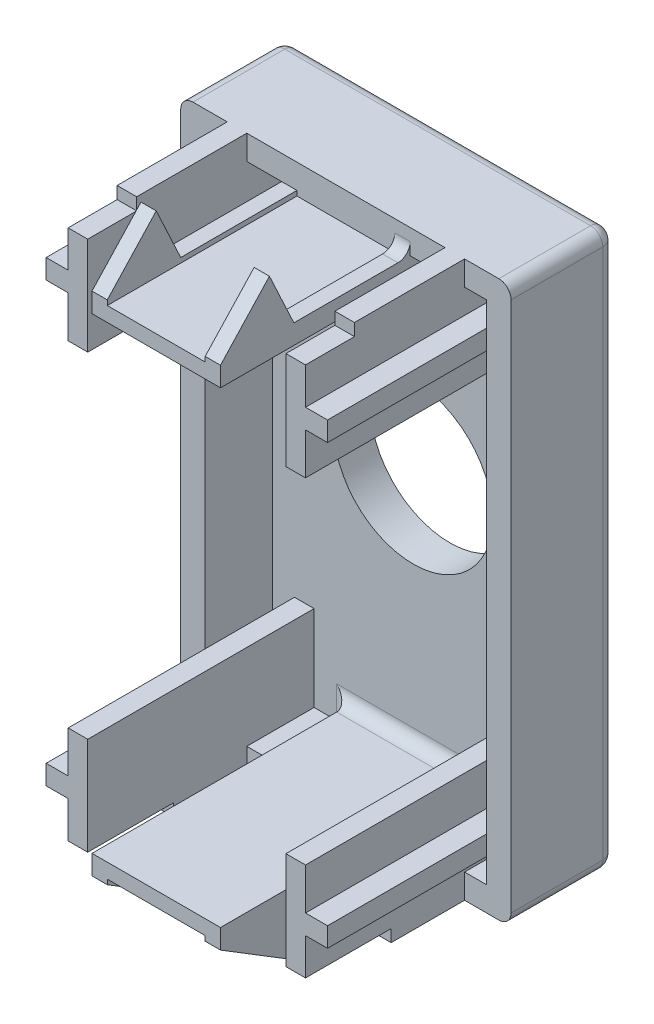
SolidWorks part; units mm, degrees
material "Сталь 3 ГОСТ 535-88"
ref_plane "Спереди" through (0, 0, 0) normal (0, 0, 1) x (1, 0, 0)
ref_plane "Сверху" through (0, 0, 0) normal (0, 1, 0) x (1, 0, 0)
ref_plane "Справа" through (0, 0, 0) normal (1, 0, 0) x (0, 0, -1)
sketch "Эскиз1" plane through (0, 0, 0) normal (0, 0, 1) x (1, 0, 0)
  line L0 (0, 22.7) -> (27, 22.7) construction
  line L1 (0, 0) -> (27, 0)
  line L2 (0, 0) -> (0, 45.4)
  line L3 (0, 45.4) -> (27, 45.4)
  line L4 (27, 0) -> (27, 45.4)
  circle A0 centre (13.5, 22.7) radius 6.5
  dimension "D3" = 13
  dimension "D1" = 27
  dimension "D2" = 45.4
extrude "Бобышка-Вытянуть1" add sketch "Эскиз1" along normal blind 8.5
ref_plane "Плоскость1" through (3, 0, 0) normal (1, 0, 0) x (0, 0, -1)
sketch "Эскиз2" plane through (3, 0, 0) normal (1, 0, 0) x (0, 0, -1)
  line L0 (0, 0) -> (0, 5) construction
  line L2 (0, 45.4) -> (0, 40.4) construction
  line L3 (0, 40.4) -> (0, 5)
  arc A0 (0, 5) -> (0, 40.4) centre (156.145, 22.7) cw
  point P3 (0, 0)
  point P9 (0, 0)
  point P10 (0, 0)
  point P11 (0, 0)
  dimension "D1" = 5
  dimension "D3" = 1
  dimension "D2" = 5
extrude "Вырез-Вытянуть1" cut sketch "Эскиз2" along normal offset from surface (21 mm away) 3 up to face at (27, 22.7, 4.25)
sketch "Эскиз3" plane through (0, 0, 8.5) normal (0, 0, 1) x (1, 0, 0)
  line L0 (25, 2) -> (25, 43.4)
  line L1 (27, 0) -> (0, 0) construction
  line L2 (27, 0) -> (27, 45.4) construction
  line L3 (27, 45.4) -> (0, 45.4) construction
  line L4 (0, 0) -> (0, 45.4) construction
  line L5 (25, 43.4) -> (2, 43.4)
  line L6 (2, 2) -> (2, 43.4)
  line L7 (25, 2) -> (2, 2)
  dimension "D1" = 2
extrude "Вырез-Вытянуть2" cut sketch "Эскиз3" against normal blind 5.5
sketch "Эскиз4" plane through (0, 0, 3) normal (0, 0, 1) x (1, 0, 0)
  line L0 (3.8, 45.4) -> (3.8, 41.4)
  line L1 (25, 43.4) -> (2, 43.4) construction
  line L2 (3.8, 41.4) -> (2, 41.4)
  line L3 (2, 43.4) -> (2, 2) construction
  line L4 (2, 41.4) -> (2, 39.8)
  line L5 (2, 39.8) -> (3.8, 39.8)
  line L6 (3.8, 39.8) -> (3.8, 36.4)
  line L7 (3.8, 36.4) -> (5.4, 36.4)
  line L8 (5.4, 36.4) -> (5.4, 45.4)
  line L10 (5.4, 45.4) -> (3.8, 45.4)
  line L11 (3.8, 39.8) -> (3.8, 41.4) construction
  line L12 (13.5, 43.4) -> (13.5, 2) construction
  line L13 (2, 2) -> (25, 2) construction
  line L14 (25, 22.7) -> (2, 22.7) construction
  line L15 (25, 2) -> (25, 43.4) construction
  line L16 (2, 43.4) -> (2, 2) construction
  line L17 (23.2, 39.8) -> (23.2, 41.4) construction
  line L18 (21.6, 45.4) -> (23.2, 45.4)
  line L19 (21.6, 36.4) -> (21.6, 45.4)
  line L20 (23.2, 36.4) -> (21.6, 36.4)
  line L21 (23.2, 39.8) -> (23.2, 36.4)
  line L22 (25, 39.8) -> (23.2, 39.8)
  line L23 (25, 41.4) -> (25, 39.8)
  line L24 (23.2, 41.4) -> (25, 41.4)
  line L25 (23.2, 45.4) -> (23.2, 41.4)
  line L26 (23.2, 5.6) -> (23.2, 4) construction
  line L27 (3.8, 5.6) -> (3.8, 4) construction
  line L28 (23.2, 0) -> (23.2, 4)
  line L29 (23.2, 4) -> (25, 4)
  line L30 (25, 4) -> (25, 5.6)
  line L31 (25, 5.6) -> (23.2, 5.6)
  line L32 (23.2, 5.6) -> (23.2, 9)
  line L33 (23.2, 9) -> (21.6, 9)
  line L34 (21.6, 9) -> (21.6, 0)
  line L35 (21.6, 0) -> (23.2, 0)
  line L36 (5.4, 0) -> (3.8, 0)
  line L37 (5.4, 9) -> (5.4, 0)
  line L38 (3.8, 9) -> (5.4, 9)
  line L39 (3.8, 5.6) -> (3.8, 9)
  line L40 (2, 5.6) -> (3.8, 5.6)
  line L41 (2, 4) -> (2, 5.6)
  line L42 (3.8, 4) -> (2, 4)
  line L43 (3.8, 0) -> (3.8, 4)
  line L44 (27, 45.4) -> (0, 45.4) construction
  dimension "D1" = 1.6
  dimension "D2" = 1.6
  dimension "D3" = 4
  dimension "D4" = 9
  dimension "D5" = 1.8
extrude "Бобышка-Вытянуть2" add sketch "Эскиз4" along normal blind 18.5
ref_plane "Плоскость2" through (13.5, 0, 0) normal (-1, 0, 0) x (0, 0, 1)
sketch "Эскиз6" plane through (13.5, 0, 0) normal (-1, 0, 0) x (0, 0, 1)
  line L0 (3, 2) -> (3, 3.6)
  line L1 (3, 9) -> (3, 2) construction
  line L2 (3, 3.6) -> (24, 3.6)
  line L3 (24, 3.6) -> (24, 2)
  line L4 (24, 2) -> (17, -2.3)
  line L5 (17, -2.3) -> (15, 2)
  line L6 (15, 2) -> (3, 2)
  line L7 (15, 2) -> (24, 2) construction
  line L8 (8.5, 22.7) -> (24, 22.7) construction
  line L10 (18, 43.4) -> (24, 43.4) construction
  line L11 (18, 43.4) -> (3, 43.4)
  line L12 (20, 47.7) -> (18, 43.4)
  line L13 (24, 43.4) -> (20, 47.7)
  line L14 (24, 41.8) -> (24, 43.4)
  line L15 (3, 41.8) -> (24, 41.8)
  line L16 (3, 43.4) -> (3, 41.8)
  line L17 (8.5, 45.4) -> (8.5, 0) construction
  point P11 (14, 22.7)
  point P12 (12, 22.7)
  point P20 (24, 22.7)
  point P21 (15, 43.4)
  point P22 (17, 47.0738)
  point P23 (11.236, 47.0738)
  point P24 (11.3535, 43.4)
  point P25 (11.6904, 43.4)
  point P26 (0, 0)
  point P27 (0, 0)
  point P28 (8.1753, 22.7)
  point P29 (8.5, 22.7)
  dimension "D1" = 1.6
  dimension "D2" = 12
  dimension "D3" = 21
  dimension "D4" = 15
  dimension "D5" = 14
  dimension "D6" = 17
  dimension "D7" = 25
  dimension "D8" = 25
  dimension "D9" = 1.6
extrude "Бобышка-Вытянуть3" add sketch "Эскиз6" along normal blind 5.25 and the other way blind 5.25
sketch "Эскиз7" plane through (3.8, 0, 0) normal (-1, 0, 0) x (0, 0, 1)
  line L0 (21.5, 4) -> (21.5, 0) construction
  line L1 (21.5, 45.4) -> (17.5, 45.4)
  line L2 (21.5, 45.4) -> (21.5, 44.4)
  line L3 (21.5, 44.4) -> (17.5, 44.4)
  line L4 (17.5, 45.4) -> (17.5, 44.4)
  line L5 (21.5, 0) -> (14.5, 0)
  line L6 (21.5, 0) -> (21.5, 1)
  line L7 (21.5, 1) -> (14.5, 1)
  line L8 (14.5, 0) -> (14.5, 1)
  line L9 (21.5, 0) -> (8.5, 0) construction
  dimension "D1" = 1
  dimension "D2" = 4
  dimension "D3" = 1
  dimension "D4" = 7
extrude "Вырез-Вытянуть3" cut sketch "Эскиз7" against normal blind 3
sketch "Эскиз8" plane through (23.2, 0, 0) normal (1, 0, 0) x (0, 0, -1)
  line L0 (-21.5, 45.4) -> (-8.5, 45.4) construction
  line L1 (-21.5, 0) -> (-14.5, 0)
  line L2 (-21.5, 0) -> (-21.5, 1)
  line L3 (-21.5, 1) -> (-14.5, 1)
  line L4 (-14.5, 0) -> (-14.5, 1)
  line L5 (-21.5, 45.4) -> (-17.5, 45.4)
  line L6 (-21.5, 45.4) -> (-21.5, 44.4)
  line L7 (-21.5, 44.4) -> (-17.5, 44.4)
  line L8 (-17.5, 45.4) -> (-17.5, 44.4)
  dimension "D1" = 1
  dimension "D2" = 1
  dimension "D3" = 7
  dimension "D4" = 4
extrude "Вырез-Вытянуть4" cut sketch "Эскиз8" against normal blind 3
sketch "Эскиз9" plane through (0, 0, 24) normal (0, 0, 1) x (1, 0, 0)
  line L0 (13.5, 2) -> (13.5, -4.1037) construction
  line L1 (18.75, 2) -> (8.25, 2) construction
  line L2 (13.5, 4.675) -> (13.5, -4.675) construction
  line L3 (18.75, 3.6) -> (8.25, 3.6) construction
  line L4 (17.5, 2.4) -> (9.5, 2.4)
  line L5 (17.5, 2.4) -> (17.5, -10.6074)
  line L6 (17.5, -10.6074) -> (9.5, -10.6074)
  line L7 (9.5, 2.4) -> (9.5, -10.6074)
  line L8 (17.5, 2.4) -> (9.5, -10.6074) construction
  line L9 (17.5, -10.6074) -> (9.5, 2.4) construction
  line L10 (0, 22.7) -> (-5.4157, 22.7) construction
  line L11 (0, 45.4) -> (0, 0) construction
  line L12 (17.5, 56.0074) -> (9.5, 43) construction
  line L13 (17.5, 43) -> (9.5, 56.0074) construction
  line L14 (13.5, 43.4) -> (13.5, 49.5037) construction
  line L15 (9.5, 43) -> (9.5, 56.0074)
  line L16 (17.5, 56.0074) -> (9.5, 56.0074)
  line L17 (17.5, 43) -> (17.5, 56.0074)
  line L18 (17.5, 43) -> (9.5, 43)
  point P22 (9.5, 56.0074)
  dimension "D1" = 8
  dimension "D2" = 1.2
extrude "Вырез-Вытянуть5" cut sketch "Эскиз9" against normal up to surface (15.5 mm away)
fillet "Скругление1" radius 1 8 edges at (0, 0, 4.25) (27, 0, 4.25) (0, 45.4, 4.25) (27, 45.4, 4.25) (13.5, 0, 0) (0, 22.7, 0) (13.5, 45.4, 0) (27, 22.7, 0)
fillet "Скругление3" radius 1 8 edges at (8.25, 2.8, 3) (18.75, 2.8, 3) (18.75, 42.6, 3) (8.25, 42.6, 3) (13.5, 41.8, 3) (18.125, 43.4, 8.5) (13.5, 3.6, 3) (8.875, 2, 8.5)
sketch "Эскиз10" plane through (0, 0, 0) normal (0, 0, -1) x (-1, 0, 0)
  line L1 (-2.0478, 41.9069) -> (-24.9298, 41.9069)
  line L2 (-2.0478, 41.9069) -> (-2.0478, 3.4123)
  line L3 (-2.0478, 3.4123) -> (-24.9298, 3.4123)
  line L4 (-24.9298, 41.9069) -> (-24.9298, 3.4123)
  circle A0 centre (-13.5, 22.7) radius 6.5
  dimension "D1" = 13
extrude "Бобышка-Вытянуть4" add sketch "Эскиз10" against normal blind 3
